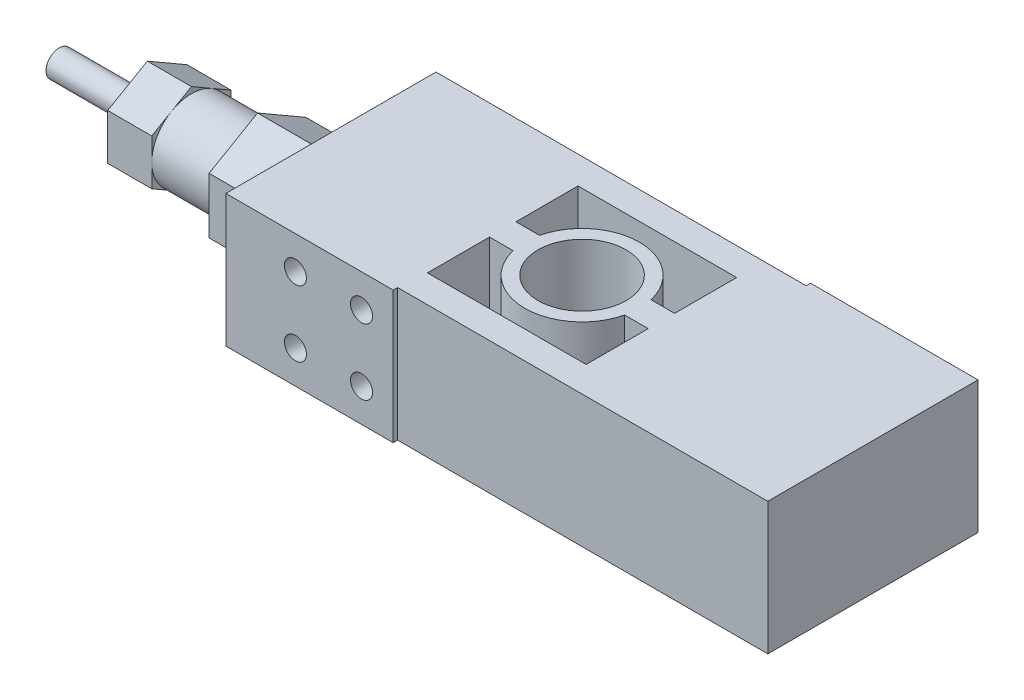
SolidWorks part; units mm, degrees
ref_plane "Ön Düzlem" through (0, 0, 0) normal (0, 0, 1) x (1, 0, 0)
ref_plane "Üst Düzlem" through (0, 0, 0) normal (0, 1, 0) x (1, 0, 0)
ref_plane "Sağ Düzlem" through (0, 0, 0) normal (1, 0, 0) x (0, 0, -1)
sketch "Çizim1" plane through (0, 0, 0) normal (0, 0, 1) x (1, 0, 0)
  line L1 (-61, 15) -> (61, 15)
  line L2 (-61, 15) -> (-61, -15)
  line L3 (-61, -15) -> (61, -15)
  line L4 (61, 15) -> (61, -15)
  line L5 (-61, 15) -> (61, -15) construction
  line L6 (-61, -15) -> (61, 15) construction
  point P0 (0, 0)
  dimension "D1" = 30
  dimension "D2" = 122
extrude "Yükseklik-Ekstrüzyon1" add sketch "Çizim1" along normal blind 46.7
sketch "Çizim2" plane through (0, 0, 0) normal (0, 0, -1) x (-1, 0, 0)
  line L0 (-61, 15) -> (61, 15) construction
  line L1 (-61, -15) -> (-23, -15)
  line L2 (-61, -15) -> (-61, 15)
  line L3 (-61, 15) -> (-23, 15)
  line L4 (-23, -15) -> (-23, 15)
  dimension "D1" = 38
extrude "Yükseklik-Ekstrüzyon2" add sketch "Çizim2" along normal blind 1
sketch "Çizim3" plane through (0, 0, -1) normal (0, 0, -1) x (-1, 0, 0)
  line L0 (-23, -15) -> (-23, 15) construction
  line L1 (-44, 7.5) -> (-29, 7.5) construction
  line L2 (-44, 7.5) -> (-44, -7.5) construction
  line L3 (-44, -7.5) -> (-29, -7.5) construction
  line L4 (-29, 7.5) -> (-29, -7.5) construction
  line L5 (-44, 7.5) -> (-29, -7.5) construction
  line L6 (-44, -7.5) -> (-29, 7.5) construction
  circle A0 centre (-29, 7.5) radius 2.5
  circle A1 centre (-44, 7.5) radius 2.5
  circle A2 centre (-44, -7.5) radius 2.5
  circle A3 centre (-29, -7.5) radius 2.5
  point P0 (-36.5, 0)
  dimension "D4" = 5
  dimension "D1" = 15
  dimension "D2" = 15
  dimension "D3" = 6
extrude "Kes-Ekstrüzyon1" cut sketch "Çizim3" against normal blind 20
cosmetic thread "Kozmetik Diş Açma1" parameters "D2"=6
cosmetic thread "Kozmetik Diş Açma2" parameters "D2"=6
cosmetic thread "Kozmetik Diş Açma3" parameters "D2"=6
cosmetic thread "Kozmetik Diş Açma4" parameters "D2"=6
sketch "Çizim4" plane through (0, -15, 0) normal (0, -1, 0) x (1, 0, 0)
  line L0 (-61, 46.7) -> (-61, 0) construction
  line L1 (18, 2) -> (-27, 2) construction
  line L2 (18, 2) -> (18, 44.7) construction
  line L3 (18, 44.7) -> (-27, 44.7) construction
  line L4 (-27, 2) -> (-27, 44.7) construction
  line L5 (18, 2) -> (-27, 44.7) construction
  line L6 (18, 44.7) -> (-27, 2) construction
  line L7 (-61, 0) -> (23, 0) construction
  line L8 (-61, 46.7) -> (61, 46.7) construction
  line L9 (-17.5, 23.35) -> (-22.5, 23.35) construction
  line L10 (13.5, 6.27) -> (-22.5, 6.27)
  line L11 (13.5, 6.27) -> (13.5, 20.35)
  line L12 (13.5, 40.43) -> (-22.5, 40.43)
  line L13 (-22.5, 6.27) -> (-22.5, 20.35)
  line L14 (13.5, 6.27) -> (-22.5, 40.43) construction
  line L15 (13.5, 40.43) -> (-22.5, 6.27) construction
  line L16 (8.5, 23.35) -> (13.5, 23.35) construction
  line L17 (-17.1491, 26.35) -> (-22.5, 26.35)
  line L18 (-17.1491, 20.35) -> (-22.5, 20.35)
  line L19 (8.1491, 20.35) -> (13.5, 20.35)
  line L20 (8.1491, 26.35) -> (13.5, 26.35)
  line L21 (8.5, 26.35) -> (13.5, 26.35) construction
  line L22 (8.5, 20.35) -> (13.5, 20.35) construction
  line L23 (-17.5, 20.35) -> (-22.5, 20.35) construction
  line L24 (-17.5, 26.35) -> (-22.5, 26.35) construction
  line L25 (13.5, 26.35) -> (13.5, 40.43)
  line L26 (-22.5, 26.35) -> (-22.5, 40.43)
  arc A0 (-17.1491, 20.35) -> (8.1491, 20.35) centre (-4.5, 23.35) ccw
  arc A1 (8.1491, 26.35) -> (-17.1491, 26.35) centre (-4.5, 23.35) ccw
  point P0 (-4.5, 23.35)
  dimension "D5" = 26
  dimension "D1" = 34
  dimension "D2" = 45
  dimension "D3" = 2
  dimension "D4" = 2
  dimension "D6" = 36
  dimension "D7" = 3
  dimension "D8" = 3
  dimension "D9" = 3
  dimension "D10" = 3
extrude "Kes-Ekstrüzyon2" cut sketch "Çizim4" against normal blind 38
sketch "Çizim5" plane through (0, -15, 0) normal (0, -1, 0) x (1, 0, 0)
  circle A0 centre (-4.5, 23.35) radius 10
  dimension "D1" = 20
extrude "Kes-Ekstrüzyon3" cut sketch "Çizim5" against normal blind 38
sketch "Çizim6" plane through (-61, 0, 0) normal (-1, 0, 0) x (0, 0, 1)
  line L1 (26, 12.7017) -> (15, 6.3509)
  line L2 (15, 6.3509) -> (15, -6.3509)
  line L3 (15, -6.3509) -> (26, -12.7017)
  line L4 (26, -12.7017) -> (37, -6.3509)
  line L5 (37, -6.3509) -> (37, 6.3509)
  line L6 (37, 6.3509) -> (26, 12.7017)
  circle A0 centre (26, 0) radius 11 construction
  dimension "D1" = 22
  dimension "D2" = 26
extrude "Yükseklik-Ekstrüzyon3" add sketch "Çizim6" along normal blind 14.5
sketch "Çizim7" plane through (-75.5, 0, 0) normal (-1, 0, 0) x (0, 0, 1)
  line L0 (15, 0) -> (37, 0) construction
  line L1 (15, 6.3509) -> (15, -6.3509) construction
  line L2 (37, -6.3509) -> (37, 6.3509) construction
  circle A0 centre (26, 0) radius 9
  dimension "D1" = 18
extrude "Yükseklik-Ekstrüzyon4" add sketch "Çizim7" along normal blind 15
sketch "Çizim8" plane through (0, 0, 46.7) normal (0, 0, 1) x (1, 0, 0)
  line L0 (-61, -15) -> (61, -15) construction
  line L1 (-23, 15) -> (-61, 15)
  line L2 (-23, 15) -> (-23, -15)
  line L3 (-23, -15) -> (-61, -15)
  line L4 (-61, 15) -> (-61, -15)
  line L5 (61, 15) -> (-61, 15) construction
  dimension "D1" = 38
extrude "Yükseklik-Ekstrüzyon5" add sketch "Çizim8" along normal blind 1
sketch "Çizim9" plane through (0, 0, 47.7) normal (0, 0, 1) x (1, 0, 0)
  line L1 (-45.2, 7.5) -> (-30.2, 7.5) construction
  line L2 (-45.2, 7.5) -> (-45.2, -7.5) construction
  line L3 (-45.2, -7.5) -> (-30.2, -7.5) construction
  line L4 (-30.2, 7.5) -> (-30.2, -7.5) construction
  line L5 (-45.2, 7.5) -> (-30.2, -7.5) construction
  line L6 (-45.2, -7.5) -> (-30.2, 7.5) construction
  line L7 (-61, -15) -> (-23, -15) construction
  line L9 (-61, -6.3509) -> (-61, 6.3509) construction
  circle A0 centre (-45.2, 7.5) radius 2.5
  circle A1 centre (-45.2, -7.5) radius 2.5
  circle A2 centre (-30.2, -7.5) radius 2.5
  circle A3 centre (-30.2, 7.5) radius 2.5
  point P0 (-37.7, 0)
  dimension "D5" = 5
  dimension "D1" = 15
  dimension "D2" = 15
  dimension "D3" = 15.8
  dimension "D4" = 15
extrude "Kes-Ekstrüzyon4" cut sketch "Çizim9" against normal blind 20
cosmetic thread "Kozmetik Diş Açma5" parameters "D2"=6
cosmetic thread "Kozmetik Diş Açma6" parameters "D2"=6
cosmetic thread "Kozmetik Diş Açma7" parameters "D2"=6
cosmetic thread "Kozmetik Diş Açma8" parameters "D2"=6
sketch "Çizim10" plane through (-90.5, 0, 0) normal (-1, 0, 0) x (0, 0, 1)
  line L1 (26, 10.3923) -> (17, 5.1962)
  line L2 (17, 5.1962) -> (17, -5.1962)
  line L3 (17, -5.1962) -> (26, -10.3923)
  line L4 (26, -10.3923) -> (35, -5.1962)
  line L5 (35, -5.1962) -> (35, 5.1962)
  line L6 (35, 5.1962) -> (26, 10.3923)
  circle A0 centre (26, 0) radius 9 construction
  dimension "D1" = 18
extrude "Yükseklik-Ekstrüzyon6" add sketch "Çizim10" along normal blind 10
sketch "Çizim11" plane through (-100.5, 0, 0) normal (-1, 0, 0) x (0, 0, 1)
  circle A0 centre (26, 0) radius 3
  dimension "D1" = 6
extrude "Yükseklik-Ekstrüzyon7" add sketch "Çizim11" along normal blind 20
